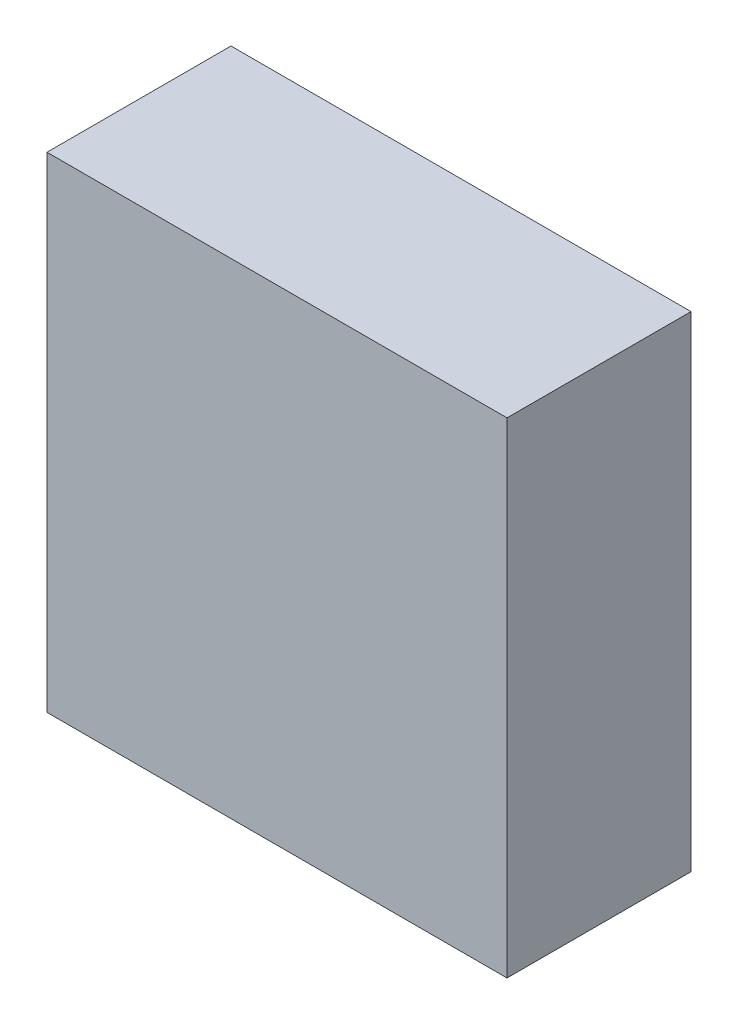
SolidWorks part; units mm, degrees
ref_plane "Front Plane" through (0, 0, 0) normal (0, 0, 1) x (1, 0, 0)
ref_plane "Top Plane" through (0, 0, 0) normal (0, 1, 0) x (1, 0, 0)
ref_plane "Right Plane" through (0, 0, 0) normal (1, 0, 0) x (0, 0, -1)
sketch "Sketch1" plane through (0, 0, 0) normal (0, 0, 1) x (1, 0, 0)
  line L1 (-27.5, -29) -> (27.5, -29)
  line L2 (-27.5, -29) -> (-27.5, 29)
  line L3 (-27.5, 29) -> (27.5, 29)
  line L4 (27.5, -29) -> (27.5, 29)
extrude "Boss-Extrude1" add sketch "Sketch1" along normal blind 22
sketch "Sketch2" plane through (0, 0, 0) normal (0, 0, 1) x (1, 0, 0)
  line L1 (-25.5, -27) -> (25.5, -27)
  line L2 (-25.5, -27) -> (-25.5, 27)
  line L3 (-25.5, 27) -> (25.5, 27)
  line L4 (25.5, -27) -> (25.5, 27)
extrude "Cut-Extrude2" cut sketch "Sketch2" along normal blind 20
